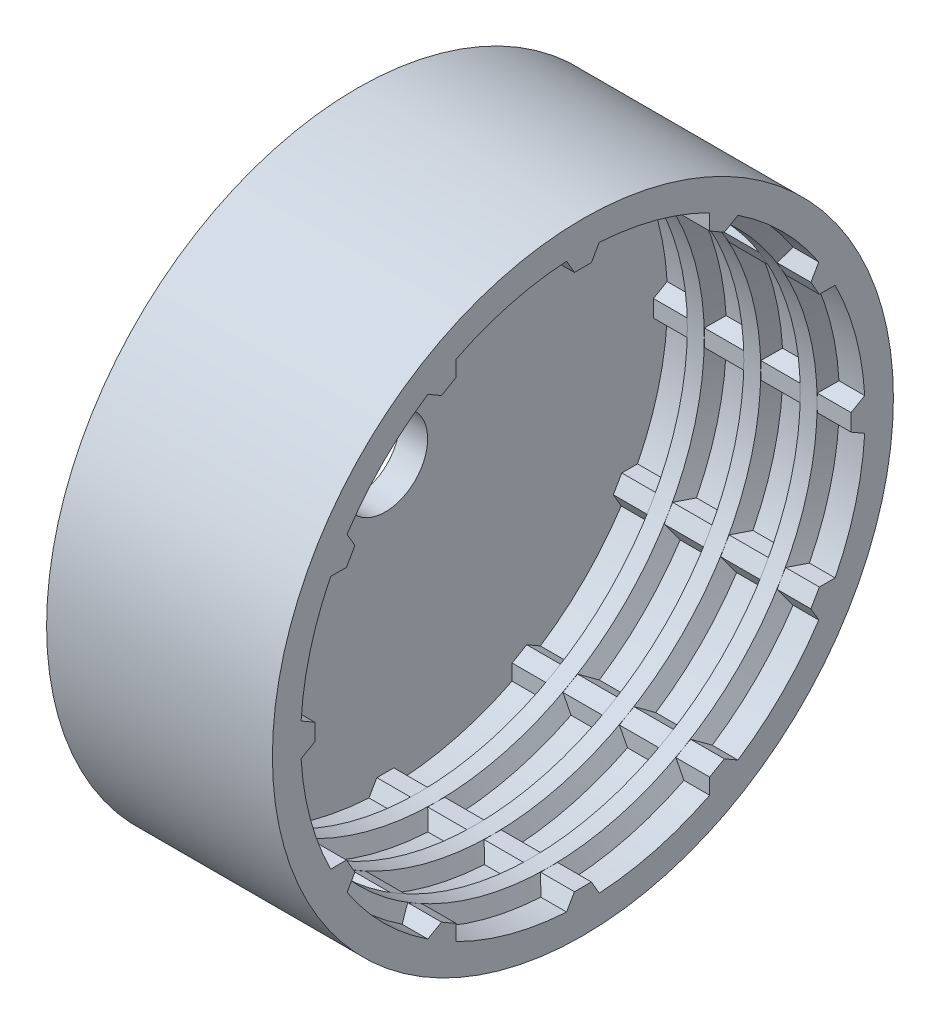
SolidWorks part; units mm, degrees
ref_plane "Front Plane" through (0, 0, 0) normal (0, 0, 1) x (1, 0, 0)
ref_plane "Top Plane" through (0, 0, 0) normal (0, 1, 0) x (1, 0, 0)
ref_plane "Right Plane" through (0, 0, 0) normal (1, 0, 0) x (0, 0, -1)
sketch "Sketch1" plane through (0, 0, 0) normal (0, 1, 0) x (1, 0, 0)
  line L0 (0, 4.7625) -> (0, 34.925)
  line L1 (0, 34.925) -> (25.4, 34.925)
  line L2 (25.4, 34.925) -> (25.4, 31.75)
  line L3 (25.4, 31.75) -> (3.175, 31.75)
  line L4 (3.175, 31.75) -> (3.175, 4.7625)
  line L8 (1.5875, 0) -> (24.5079, 0) construction
  line L9 (0, 4.7625) -> (3.175, 4.7625)
  line L15 (13.335, 30.1625) -> (15.24, 30.1625)
  line L16 (15.24, 30.1625) -> (16.1565, 31.75)
  line L17 (6.985, 30.1625) -> (6.0685, 31.75)
  line L18 (6.985, 33.3375) -> (8.89, 33.3375)
  line L19 (6.985, 33.3375) -> (6.985, 30.1625)
  line L20 (6.985, 30.1625) -> (8.89, 30.1625)
  line L21 (8.89, 33.3375) -> (8.89, 30.1625)
  line L22 (6.985, 33.3375) -> (8.89, 30.1625) construction
  line L23 (6.985, 30.1625) -> (8.89, 33.3375) construction
  line L28 (13.335, 33.3375) -> (15.24, 30.1625) construction
  line L29 (13.335, 30.1625) -> (12.4185, 31.75)
  line L30 (8.89, 30.1625) -> (9.8065, 31.75)
  line L31 (13.335, 33.3375) -> (13.335, 30.1625)
  line L32 (13.335, 30.1625) -> (15.24, 33.3375) construction
  line L33 (13.335, 33.3375) -> (15.24, 33.3375)
  line L34 (15.24, 33.3375) -> (15.24, 30.1625)
  line L35 (19.685, 30.1625) -> (21.59, 30.1625)
  line L36 (21.59, 30.1625) -> (22.5065, 31.75)
  line L37 (19.685, 33.3375) -> (21.59, 30.1625) construction
  line L38 (19.685, 30.1625) -> (18.7685, 31.75)
  line L39 (19.685, 33.3375) -> (19.685, 30.1625)
  line L40 (19.685, 30.1625) -> (21.59, 33.3375) construction
  line L41 (19.685, 33.3375) -> (21.59, 33.3375)
  line L42 (21.59, 33.3375) -> (21.59, 30.1625)
  line L43 (6.985, 30.1625) -> (13.335, 30.1625) construction
  point P13 (7.9375, 31.75)
  dimension "D8" = 4.7625
  dimension "D2" = 63.5
  dimension "D3" = 3.175
  dimension "D4" = 3.175
  dimension "D5" = 30
  dimension "D6" = 9.525
  dimension "D7" = 1.905
  dimension "D9" = 3.175
  dimension "D10" = 6.35
  dimension "D11" = 3
  dimension "D12" = 22.225
revolve "Revolve1" add sketch "Sketch1" angle 360 about L8
sketch "Sketch2" plane through (3.175, 0, 0) normal (1, 0, 0) x (0, 0, -1)
  line L0 (0, 31.75) -> (0, 30.1625) construction
  line L1 (-0.9525, 30.1625) -> (0.9525, 30.1625)
  line L2 (-0.9525, 30.1625) -> (-1.8383, 31.6967)
  line L3 (0.9525, 30.1625) -> (1.8383, 31.6967)
  line L4 (-0.9525, 30.1625) -> (-0.9525, 31.7357) construction
  line L5 (0.9525, 30.1625) -> (0.9525, 31.7357) construction
  circle A0 centre (0, 0) radius 31.75 construction
  arc A6 (-1.8383, 31.6967) -> (1.8383, 31.6967) centre (0, 0) cw
  circle A7 centre (0, 0) radius 30.1625 construction
  point P12 (0, 30.1625)
  dimension "D1" = 1.905
  dimension "D2" = 30
  dimension "D3" = 30
extrude "Boss-Extrude1" add sketch "Sketch2" along normal up to surface (22.225 mm away) up to face at (25.4, 0, 31.75)
pattern_circular "CirPattern1" count 12 every 30 about axis through (0, 0, 0) along (1, 0, 0) of "Boss-Extrude1"
